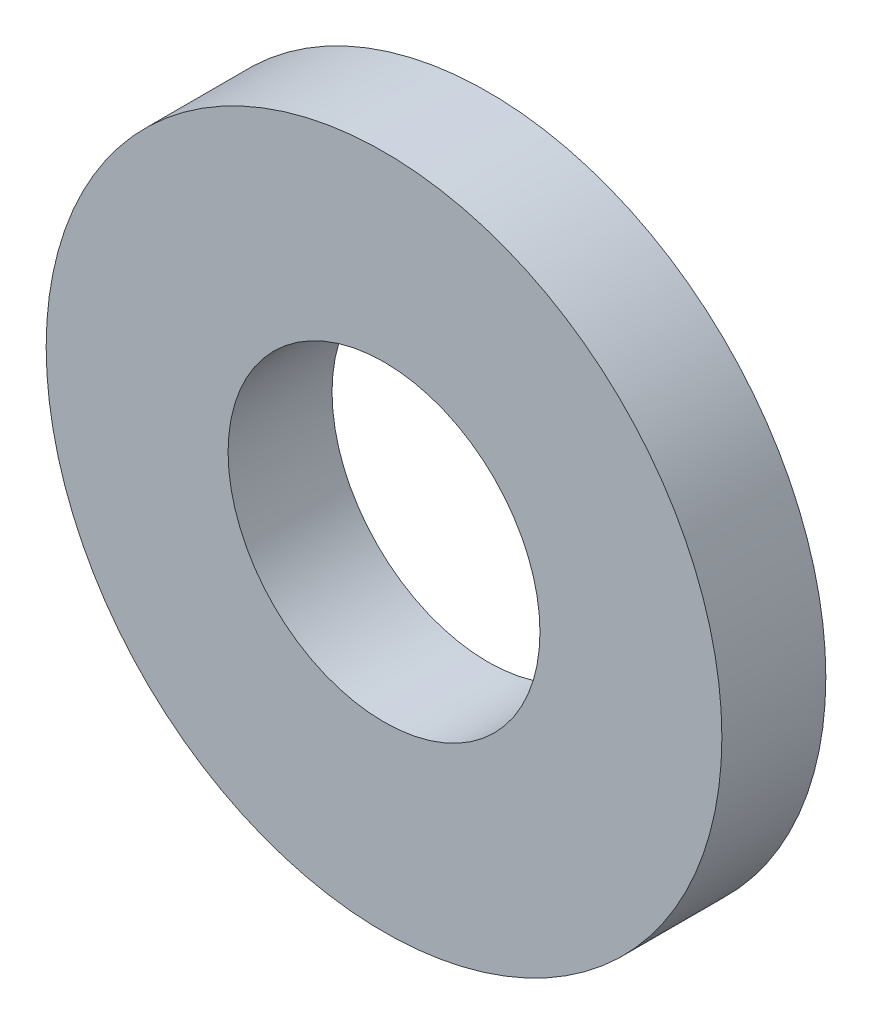
SolidWorks part; units mm, degrees
ref_plane "前视基准面" through (0, 0, 0) normal (0, 0, 1) x (1, 0, 0)
ref_plane "上视基准面" through (0, 0, 0) normal (0, 1, 0) x (1, 0, 0)
ref_plane "右视基准面" through (0, 0, 0) normal (1, 0, 0) x (0, 0, -1)
sketch "草图1" plane through (0, 0, 0) normal (0, 0, 1) x (1, 0, 0)
  circle A0 centre (0, 0) radius 6
  circle A1 centre (0, 0) radius 13
  dimension "D1" = 12
  dimension "D2" = 26
extrude "凸台-拉伸1" add sketch "草图1" along normal blind 4
